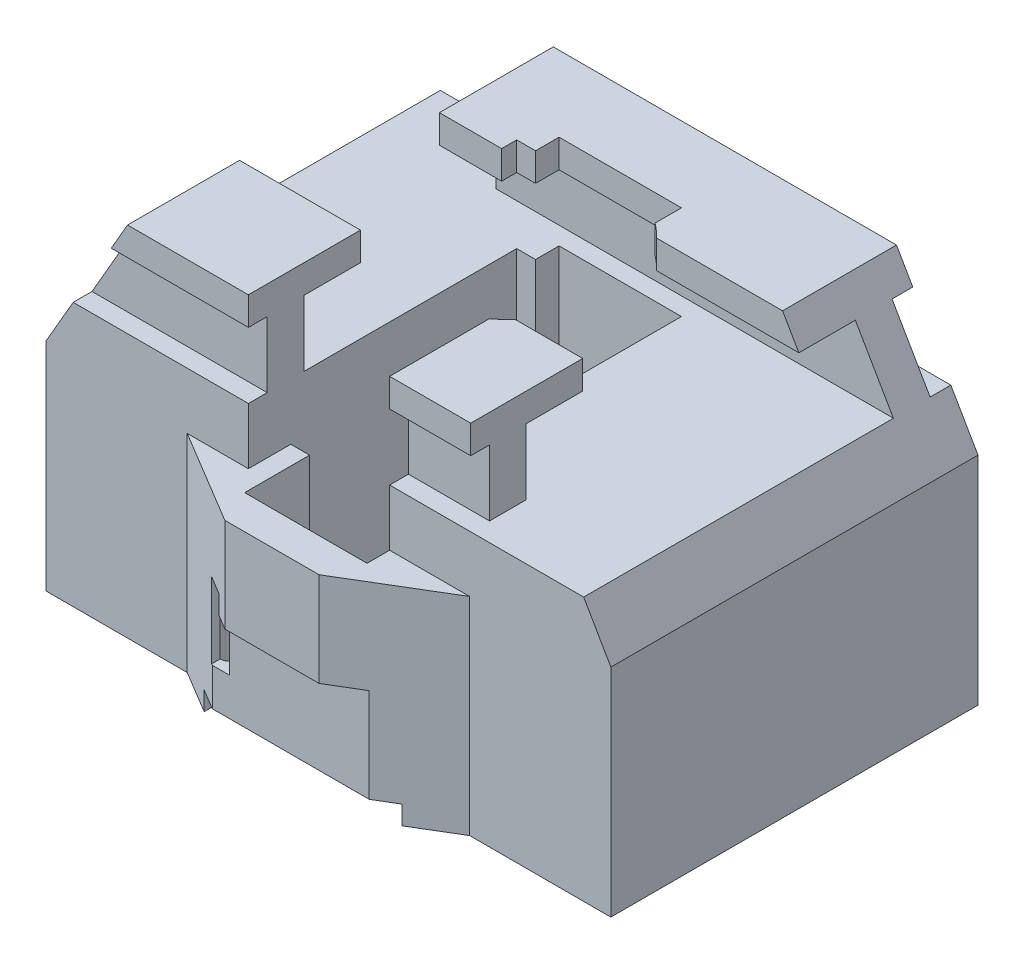
SolidWorks part; units mm, degrees
ref_plane "Front Plane" through (0, 0, 0) normal (0, 0, 1) x (1, 0, 0)
ref_plane "Top Plane" through (0, 0, 0) normal (0, 1, 0) x (1, 0, 0)
ref_plane "Right Plane" through (0, 0, 0) normal (1, 0, 0) x (0, 0, -1)
sketch "Sketch1" plane through (0, 0, 0) normal (0, 1, 0) x (1, 0, 0)
  line L1 (-60, 45) -> (0, 45)
  line L2 (-60, 45) -> (-60, 0)
  line L3 (-60, 0) -> (0, 0)
  line L4 (0, 45) -> (0, 0)
  dimension "D1" = 60
  dimension "D2" = 45
extrude "Boss-Extrude1" add sketch "Sketch1" along normal blind 30
sketch "Sketch2" plane through (0, 0, 0) normal (0, -1, 0) x (-1, 0, 0)
  line L0 (60, 45) -> (60, 0) construction
  line L1 (50.75, 13) -> (44.25, 13)
  line L2 (50.75, 13) -> (50.75, 29)
  line L3 (50.75, 29) -> (44.25, 29)
  line L4 (44.25, 13) -> (44.25, 29)
  line L5 (16.25, 13) -> (9.75, 13)
  line L6 (16.25, 13) -> (16.25, 29)
  line L7 (16.25, 29) -> (9.75, 29)
  line L8 (9.75, 13) -> (9.75, 29)
  line L10 (0, 0) -> (0, 45) construction
  line L12 (0, 45) -> (60, 45) construction
  dimension "D1" = 16
  dimension "D2" = 6.5
  dimension "D3" = 9.25
  dimension "D4" = 6.5
  dimension "D5" = 16
  dimension "D6" = 9.75
  dimension "D7" = 16
extrude "Cut-Extrude1" cut sketch "Sketch2" against normal blind 20
chamfer "Chamfer1" distance 5 angle 5 4 edges at (-16.25, 20, -21) (-9.75, 20, -21) (-50.75, 20, -21) (-44.25, 20, -21)
chamfer "Chamfer2" distance 5 angle 50 4 edges at (-47.5, 20, -29) (-13, 20, -29) (-13, 20, -13) (-47.5, 20, -13)
sketch "Sketch4" plane through (0, 0, -45) normal (0, 0, -1) x (-1, 0, 0)
  line L0 (11.5, 0) -> (28.3, 0)
  line L1 (0, 0) -> (60, 0) construction
  arc A0 (28.3, 0) -> (42.6119, 6.1301) centre (38.1836, -3.3031) cw
  arc A1 (42.6119, 6.1301) -> (46.2306, 12.0745) centre (44.0992, 9.2984) ccw
  arc A2 (46.2306, 12.0745) -> (11.5, 0) centre (32.8331, -5.3756) ccw
  dimension "D3" = 3.5
  dimension "D4" = 10.4209
  dimension "D7" = 22
  dimension "D1" = 16.8
  dimension "D2" = 11.5
  dimension "D5" = 3.3031
  dimension "D6" = 9.2984
extrude "Cut-Extrude2" cut sketch "Sketch4" against normal blind 10
chamfer "Chamfer3" distance 3 distance2 1.5 8 edges at (-13, 0, -13) (-9.75, 0, -21) (-13, 0, -29) (-16.25, 0, -21) (-47.5, 0, -29) (-44.25, 0, -21) (-47.5, 0, -13) (-50.75, 0, -21)
sketch "Sketch5" plane through (-60, 0, 0) normal (-1, 0, 0) x (0, 0, 1)
  line L0 (0, 30) -> (0, 0) construction
  line L1 (-45, 30) -> (0, 30)
  line L2 (-45, 30) -> (-45, 22)
  line L4 (0, 30) -> (0, 0)
  line L5 (-45, 22) -> (-6, 22)
  line L6 (-6, 22) -> (-6, 0)
  line L7 (-45, 0) -> (0, 0) construction
  line L8 (-6, 0) -> (0, 0)
  dimension "D1" = 8
extrude "Cut-Extrude3" cut sketch "Sketch5" against normal up to next
sketch "Sketch6" plane through (0, 0, 0) normal (0, -1, 0) x (-1, 0, 0)
  line L1 (44.25, 37) -> (16.25, 37)
  line L2 (44.25, 37) -> (44.25, 6)
  line L3 (44.25, 6) -> (16.25, 6)
  line L4 (16.25, 37) -> (16.25, 6)
  line L5 (44.25, 29) -> (44.25, 13) construction
  line L6 (0, 6) -> (60, 6) construction
  line L7 (16.25, 13) -> (16.25, 29) construction
  dimension "D1" = 31
extrude "Cut-Extrude4" cut sketch "Sketch6" against normal blind 1
sketch "Sketch12" plane through (0, 0, 0) normal (0, -1, 0) x (1, 0, 0)
  line L0 (-45, -6) -> (-35, 0)
  line L1 (-44.25, -6) -> (-60, -6) construction
  line L2 (-35, 0) -> (-25, 0)
  line L3 (-25, 0) -> (-15, -6)
  line L4 (-15, -6) -> (-45, -6)
  point P7 (-36.3267, 0)
  dimension "D1" = 30
  dimension "D2" = 15
  dimension "D3" = 6
  dimension "D4" = 10
  dimension "D5" = 10
extrude "Boss-Extrude2" add sketch "Sketch12" against normal up to surface (22 mm away) up to face at (-30, 22, -25.5)
sketch "Sketch7" plane through (0, 22, 0) normal (0, 1, 0) x (1, 0, 0)
  line L1 (-23.5, 8.6) -> (-36.5, 8.6)
  line L2 (-23.5, 8.6) -> (-23.5, 32)
  line L3 (-23.5, 32) -> (-36.5, 32)
  line L4 (-36.5, 8.6) -> (-36.5, 32)
  line L6 (0, 45) -> (-60, 45) construction
  line L9 (0, 6) -> (0, 45) construction
  circle A0 centre (-30, 25.5) radius 1.6355 construction
  dimension "D5" = 3.2709
  dimension "D1" = 13
  dimension "D2" = 23.5
  dimension "D3" = 19.5
  dimension "D4" = 30
  dimension "D6" = 16.9
  dimension "D7" = 6.5
extrude "Cut-Extrude5" cut sketch "Sketch7" against normal up to next
sketch "Sketch8" plane through (0, 1, 0) normal (0, -1, 0) x (1, 0, 0)
  line L1 (-36.5, -8.6) -> (-23.5, -8.6)
  line L2 (-36.5, -8.6) -> (-36.5, -3.6)
  line L3 (-36.5, -3.6) -> (-23.5, -3.6)
  line L4 (-23.5, -8.6) -> (-23.5, -3.6)
  line L5 (-36.5, -8.6) -> (-36.5, -32) construction
  line L6 (-23.5, -32) -> (-36.5, -32)
  line L7 (-23.5, -32) -> (-23.5, -37)
  line L8 (-23.5, -37) -> (-36.5, -37)
  line L9 (-36.5, -32) -> (-36.5, -37)
  line L10 (-23.5, -32) -> (-23.5, -8.6) construction
  point P5 (0, 0)
  point P6 (0, 0)
  point P16 (0, 0)
  dimension "D1" = 5
  dimension "D2" = 5
extrude "Cut-Extrude6" cut sketch "Sketch8" against normal up to next from offset 15.6 offset against normal yes
sketch "Sketch10" plane through (0, 22, 0) normal (0, 1, 0) x (1, 0, 0)
  line L0 (-27.5, 32) -> (-27.5, 34.5)
  line L1 (-23.5, 32) -> (-36.5, 32) construction
  line L2 (-27.5, 34.5) -> (-38.5, 34.5)
  line L3 (-38.5, 34.5) -> (-38.5, 10.5)
  line L4 (-38.5, 10.5) -> (-36.5, 10.5)
  line L5 (-36.5, 37) -> (-36.5, 3.6) construction
  line L6 (-36.5, 10.5) -> (-36.5, 32)
  line L7 (-36.5, 32) -> (-27.5, 32)
  dimension "D1" = 2.5
  dimension "D2" = 9
  dimension "D3" = 11
  dimension "D4" = 24
extrude "Cut-Extrude7" cut sketch "Sketch10" against normal up to next
sketch "Sketch13" plane through (0, 22, 0) normal (0, 1, 0) x (1, 0, 0)
  line L0 (-60, 45) -> (0, 45)
  line L1 (0, 45) -> (0, 6)
  line L2 (0, 6) -> (-15, 6)
  line L3 (-15, 6) -> (-23.5, 6)
  line L4 (-23.5, 3.6) -> (-23.5, 37) construction
  line L5 (-23.5, 6) -> (-23.5, 37)
  line L6 (-23.5, 37) -> (-36.5, 37)
  line L7 (-36.5, 37) -> (-36.5, 34.5)
  line L8 (-36.5, 34.5) -> (-38.5, 34.5)
  line L9 (-38.5, 34.5) -> (-38.5, 6)
  line L10 (-38.5, 6) -> (-60, 6)
  line L11 (-60, 6) -> (-60, 45)
extrude "Boss-Extrude3" add sketch "Sketch13" along normal blind 16
chamfer "Chamfer6" distance 15 angle 30 2 edges at (-60, 38, -25.5) (0, 38, -25.5)
sketch "Sketch14" plane through (0, 38, 0) normal (0, 1, 0) x (1, 0, 0)
  line L0 (-38.5, 6) -> (-38.5, 34.5) construction
  line L1 (-36.5, 37) -> (-23.5, 37) construction
  circle A0 centre (-30.1, 25.4) radius 11
  point P3 (0, 0)
  dimension "D1" = 22
  dimension "D2" = 8.4
  dimension "D3" = 11.6
extrude "Cut-Extrude8" cut sketch "Sketch14" against normal blind 10
sketch "Sketch15" plane through (0, 38, 0) normal (0, 1, 0) x (1, 0, 0)
  line L1 (-65.1, 32.9) -> (4.9, 32.9)
  line L2 (-65.1, 32.9) -> (-65.1, 17.9)
  line L3 (-65.1, 17.9) -> (4.9, 17.9)
  line L4 (4.9, 32.9) -> (4.9, 17.9)
  arc A0 (-23.5, 16.6) -> (-23.5, 34.2) centre (-30.1, 25.4) ccw construction
  dimension "D1" = 15
  dimension "D2" = 7.5
  dimension "D3" = 70
  dimension "D4" = 35
extrude "Cut-Extrude9" cut sketch "Sketch15" against normal up to surface (10 mm away) up to face at (-39.8, 28, -25.4)
sketch "Sketch16" plane through (-38.5, 0, 0) normal (1, 0, 0) x (0, 0, -1)
  line L0 (6, 38) -> (6, 22) construction
  line L1 (17.9, 28) -> (11.9, 28)
  line L2 (17.9, 28) -> (17.9, 35)
  line L3 (17.9, 35) -> (11.9, 35)
  line L4 (11.9, 28) -> (11.9, 35)
  line L5 (6, 28) -> (8, 28)
  line L6 (6, 28) -> (6, 35)
  line L7 (6, 35) -> (8, 35)
  line L8 (8, 28) -> (8, 35)
  dimension "D1" = 2
  dimension "D2" = 6
  dimension "D3" = 7
  dimension "D4" = 7
extrude "Cut-Extrude10" cut sketch "Sketch16" against normal through all both and the other way through all
sketch "Sketch17" plane through (-38.5, 0, 0) normal (1, 0, 0) x (0, 0, -1)
  line L0 (45, 23) -> (45, 38) construction
  line L1 (32.9, 28) -> (38.9, 28)
  line L2 (32.9, 28) -> (32.9, 35)
  line L3 (32.9, 35) -> (38.9, 35)
  line L4 (38.9, 28) -> (38.9, 35)
  line L5 (45, 28) -> (42.8, 28)
  line L6 (45, 28) -> (45, 35)
  line L7 (45, 35) -> (42.8, 35)
  line L8 (42.8, 28) -> (42.8, 35)
  dimension "D1" = 7
  dimension "D2" = 6
  dimension "D3" = 3.9
extrude "Cut-Extrude11" cut sketch "Sketch17" against normal through all both and the other way through all
sketch "Sketch18" plane through (0, 0, 0) normal (0, -1, 0) x (1, 0, 0)
  line L1 (-40.5, 2) -> (-19.5, 2)
  line L2 (-40.5, 2) -> (-40.5, -6)
  line L3 (-40.5, -6) -> (-19.5, -6)
  line L4 (-19.5, 2) -> (-19.5, -6)
  dimension "D1" = 21
  dimension "D2" = 4.5
  dimension "D3" = 8
  dimension "D4" = 0
extrude "Cut-Extrude12" cut sketch "Sketch18" against normal blind 2
sketch "Sketch19" plane through (0, 2, 0) normal (0, -1, 0) x (1, 0, 0)
  line L0 (-40.5, -3.3) -> (-40.5, -6) construction
  line L1 (-19.5, -6) -> (-40.5, -6) construction
  line L2 (-35, 0) -> (-25, 0) construction
  line L3 (-39.1705, 3.1892) -> (-20.8295, 3.1892)
  line L4 (-39.1705, 3.1892) -> (-39.1705, -2)
  line L5 (-39.1705, -2) -> (-20.8295, -2)
  line L6 (-20.8295, 3.1892) -> (-20.8295, -2)
  circle A0 centre (-38.5, -4) radius 1
  circle A1 centre (-22.5, -4) radius 1
  dimension "D1" = 2
  dimension "D2" = 16
  dimension "D3" = 2
  dimension "D4" = 2
  dimension "D5" = 2
extrude "Cut-Extrude13" cut sketch "Sketch19" against normal blind 10
sketch "Sketch20" plane through (0, 0, -10.5) normal (0, 0, -1) x (-1, 0, 0)
  line L0 (38.5, 1) -> (38.5, 22) construction
  line L1 (38.5, 14) -> (36.5, 14)
  line L2 (38.5, 14) -> (38.5, 6)
  line L3 (38.5, 6) -> (36.5, 6)
  line L4 (36.5, 14) -> (36.5, 6)
  line L5 (36.5, 1) -> (36.5, 22) construction
  line L6 (36.5, 1) -> (38.5, 1) construction
  point P10 (37.5, 1)
  dimension "D1" = 5
  dimension "D2" = 8
extrude "Cut-Extrude14" cut sketch "Sketch20" against normal up to next
sketch "Sketch21" plane through (0, 38, 0) normal (0, 1, 0) x (1, 0, 0)
  line L0 (-2.8868, 6) -> (-2.8868, 8) construction
  line L1 (-61.9141, 51.6985) -> (-45.1132, 51.6985)
  line L2 (-61.9141, 51.6985) -> (-61.9141, 28.5299)
  line L3 (-61.9141, 28.5299) -> (-45.1132, 28.5299)
  line L4 (-45.1132, 51.6985) -> (-45.1132, 28.5299)
  line L5 (10.427, -5.5418) -> (-14.8868, -5.5418)
  line L6 (10.427, -5.5418) -> (10.427, 21.7171)
  line L7 (10.427, 21.7171) -> (-14.8868, 21.7171)
  line L8 (-14.8868, -5.5418) -> (-14.8868, 21.7171)
  dimension "D1" = 12
  dimension "D2" = 12
extrude "Cut-Extrude15" cut sketch "Sketch21" against normal up to surface (10 mm away) up to face at (-30, 28, -43.9)
equation "\"D2@Sketch12\"=(60-\"D1@Sketch12\")/2"
equation "\"D5@Sketch12\"=(\"D1@Sketch12\"-\"D4@Sketch12\")/2"
equation "\"D2@Sketch15\"=\"D1@Sketch15\"/2"
equation "\"D4@Sketch16\"=\"D3@Sketch16\""
equation "\"D2@Sketch18\"=(30-\"D1@Sketch18\")/2"
equation "\"D3@Sketch19\"=(20-\"D2@Sketch19\")/2"
equation "\"D4@Sketch19\"=\"D3@Sketch19\""
